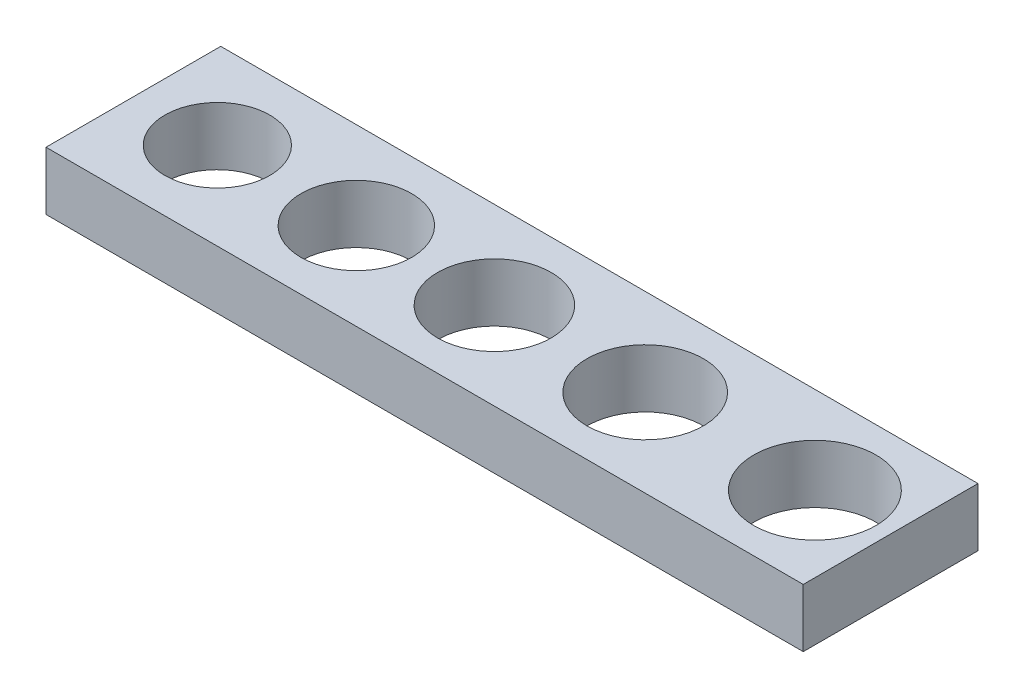
SolidWorks part; units mm, degrees
ref_plane "Front" through (0, 0, 0) normal (0, 0, 1) x (1, 0, 0)
ref_plane "Top" through (0, 0, 0) normal (0, 1, 0) x (1, 0, 0)
ref_plane "Right" through (0, 0, 0) normal (1, 0, 0) x (0, 0, -1)
sketch "Sketch1" plane through (0, 0, 0) normal (0, 1, 0) x (1, 0, 0)
  line L1 (-32.5, -7.5) -> (32.5, -7.5)
  line L2 (-32.5, -7.5) -> (-32.5, 7.5)
  line L3 (-32.5, 7.5) -> (32.5, 7.5)
  line L4 (32.5, -7.5) -> (32.5, 7.5)
  line L5 (-32.5, -7.5) -> (32.5, 7.5) construction
  line L6 (-32.5, 7.5) -> (32.5, -7.5) construction
  point P0 (0, 0)
  dimension "D1" = 65
  dimension "D2" = 15
extrude "Boss-Extrude1" add sketch "Sketch1" along normal blind 5
sketch "Sketch2" plane through (0, 5, 0) normal (0, 1, 0) x (1, 0, 0)
  line L0 (-32.5, 0) -> (32.5, 0) construction
  line L1 (-32.5, 7.5) -> (-32.5, -7.5) construction
  line L2 (32.5, -7.5) -> (32.5, 7.5) construction
  circle A0 centre (-13.3624, 0) radius 4.75
  circle A1 centre (11.4338, 0) radius 5
  circle A2 centre (25.9987, 0) radius 5.25
  circle A3 centre (-25.2916, 0) radius 4.5
  circle A4 centre (-1.5118, 0) radius 4.875
  point P12 (0, 0)
  point P13 (-13.3624, 0)
  dimension "D1" = 9.5
  dimension "D2" = 10
  dimension "D3" = 10.5
  dimension "D4" = 9
  dimension "D5" = 9.75
extrude "Cut-Extrude1" cut sketch "Sketch2" against normal blind 5
